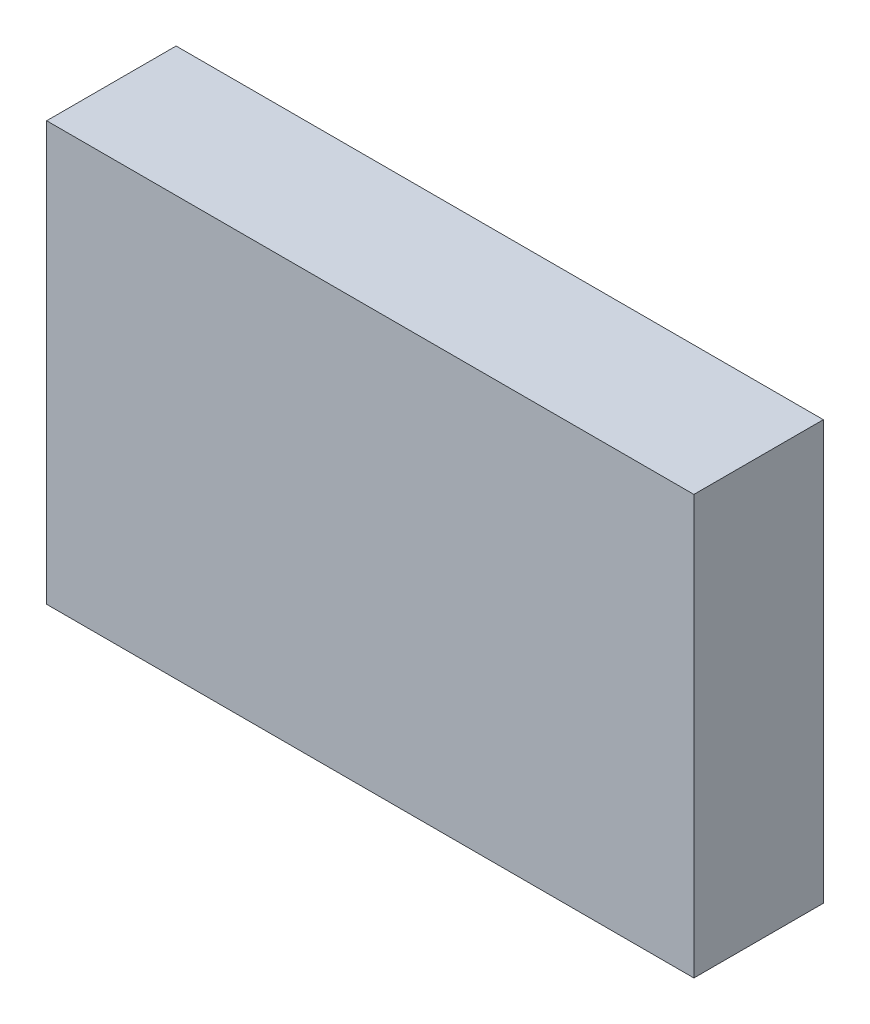
SolidWorks part; units mm, degrees
ref_plane "Front Plane" through (0, 0, 0) normal (0, 0, 1) x (1, 0, 0)
ref_plane "Top Plane" through (0, 0, 0) normal (0, 1, 0) x (1, 0, 0)
ref_plane "Right Plane" through (0, 0, 0) normal (1, 0, 0) x (0, 0, -1)
sketch "Sketch1" plane through (0, 0, 0) normal (0, 0, 1) x (1, 0, 0)
  line L1 (-38.2842, 25.5894) -> (46.7158, 25.5894)
  line L2 (-38.2842, 25.5894) -> (-38.2842, -29.4106)
  line L3 (-38.2842, -29.4106) -> (46.7158, -29.4106)
  line L4 (46.7158, 25.5894) -> (46.7158, -29.4106)
  dimension "D1" = 85
  dimension "D2" = 55
extrude "Boss-Extrude1" add sketch "Sketch1" along normal blind 17
